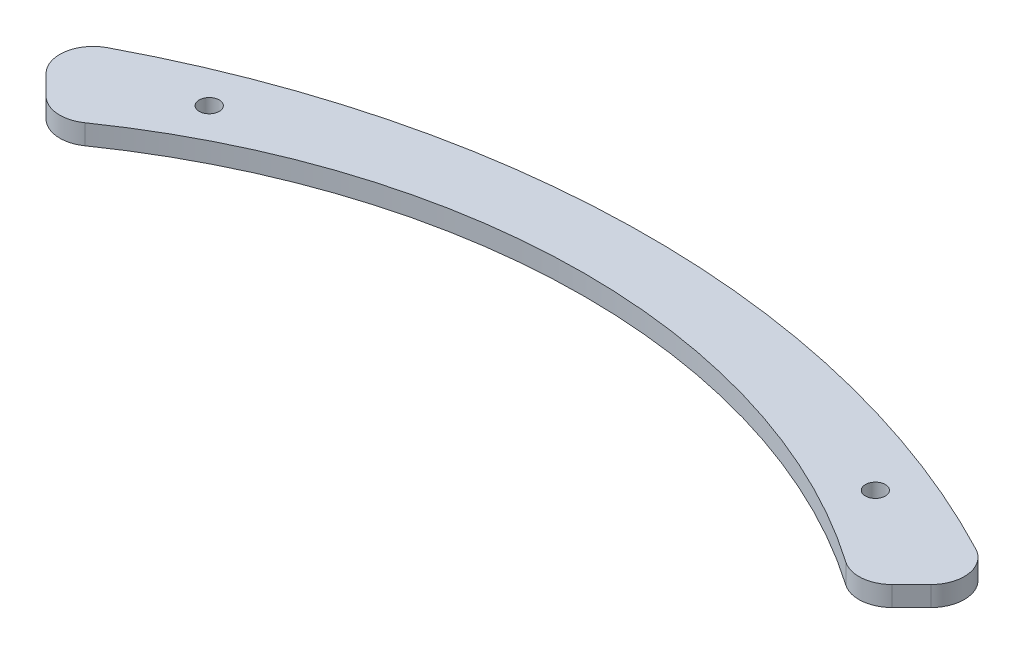
SolidWorks part; units mm, degrees
material "1060 Alloy"
ref_plane "Front Plane" through (0, 0, 0) normal (0, 0, 1) x (1, 0, 0)
ref_plane "Top Plane" through (0, 0, 0) normal (0, 1, 0) x (1, 0, 0)
ref_plane "Right Plane" through (0, 0, 0) normal (1, 0, 0) x (0, 0, -1)
sketch "Sketch1" plane through (0, 0, 0) normal (0, 1, 0) x (1, 0, 0)
  line L0 (-71.1027, 120.6002) -> (-60.4961, 109.9936)
  line L1 (71.1027, 120.6002) -> (60.4961, 109.9936)
  line L3 (0, 0) -> (-117.9329, 117.9329) construction
  line L4 (0, 0) -> (118.2874, 118.2874) construction
  line L5 (0, 0) -> (0, 174.1104) construction
  line L6 (-15, 129.1317) -> (15, 129.1317) construction
  line L7 (-15, 129.1317) -> (-15, 118.1317) construction
  line L8 (-15, 118.1317) -> (15, 118.1317) construction
  line L9 (15, 129.1317) -> (15, 118.1317) construction
  arc A0 (-71.1027, 120.6002) -> (71.1027, 120.6002) centre (0, 0) cw
  arc A1 (-60.4961, 109.9936) -> (60.4961, 109.9936) centre (0, 30.3681) cw
  circle A2 centre (0, 0) radius 130 construction
  dimension "D1" = 140
  dimension "D6" = 100
  dimension "D7" = 10
  dimension "D2" = 15
  dimension "D3" = 45
  dimension "D4" = 35
  dimension "D5" = 35
  dimension "D8" = 11
  dimension "D9" = 30
extrude "Boss-Extrude1" add sketch "Sketch1" along normal blind 3
fillet "Fillet1" radius 5 4 edges at (71.1027, 1.5, -120.6002) (60.4961, 1.5, -109.9936) (-71.1027, 1.5, -120.6002) (-60.4961, 1.5, -109.9936)
sketch "Sketch2" plane through (0, 3, 0) normal (0, 1, 0) x (1, 0, 0)
  circle A0 centre (-50, 124) radius 1.5
  circle A1 centre (50, 124) radius 1.5
  dimension "D1" = 3
  dimension "D2" = 124
  dimension "D3" = 50
  dimension "D4" = 50
extrude "Cut-Extrude1" cut sketch "Sketch2" against normal up to next
